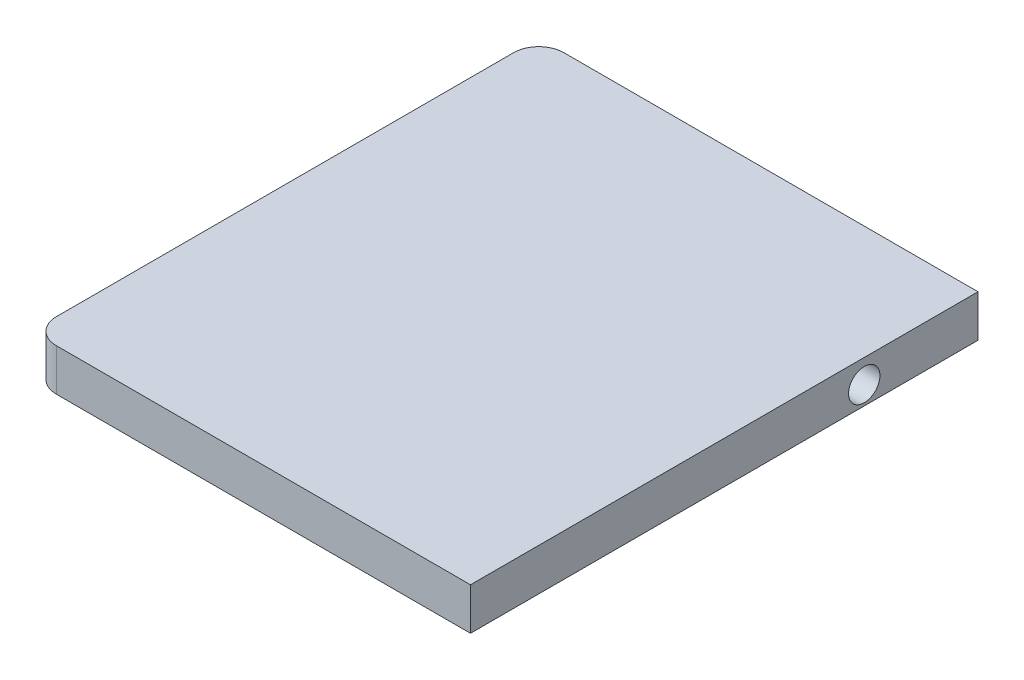
SolidWorks part; units mm, degrees
material "PLA"
ref_plane "Front Plane" through (0, 0, 0) normal (0, 0, 1) x (1, 0, 0)
ref_plane "Top Plane" through (0, 0, 0) normal (0, 1, 0) x (1, 0, 0)
ref_plane "Right Plane" through (0, 0, 0) normal (1, 0, 0) x (0, 0, -1)
sketch "Sketch1" plane through (0, 0, 0) normal (0, 1, 0) x (1, 0, 0)
  line L1 (22.225, -25.6794) -> (-22.225, -25.6794)
  line L2 (22.225, -25.6794) -> (22.225, 25.6794)
  line L3 (22.225, 25.6794) -> (-22.225, 25.6794)
  line L4 (-22.225, -25.6794) -> (-22.225, 25.6794)
  line L5 (22.225, -25.6794) -> (-22.225, 25.6794) construction
  line L6 (22.225, 25.6794) -> (-22.225, -25.6794) construction
  point P0 (0, 0)
  dimension "D1" = 51.3588
  dimension "D2" = 44.45
extrude "Boss-Extrude1" add sketch "Sketch1" along normal blind 4.7625
sketch "Sketch2" plane through (22.225, 0, 0) normal (1, 0, 0) x (0, 0, -1)
  line L0 (14.17, 4.7625) -> (14.17, 0)
  line L1 (-25.6794, 4.7625) -> (25.6794, 4.7625) construction
  line L2 (-25.6794, 0) -> (25.6794, 0) construction
  line L3 (25.6794, 4.7625) -> (25.6794, 0) construction
  circle A0 centre (14.17, 2.3813) radius 1.5875
  point P11 (14.17, 2.3813)
  dimension "D2" = 3.175
  dimension "D1" = 11.5094
extrude "Cut-Extrude1" cut sketch "Sketch2" against normal blind 29.9402 contours L0 A0 | L0 A0
fillet "Fillet1" radius 2.54 2 edges at (-22.225, 2.3813, -25.6794) (-22.225, 2.3813, 25.6794)
chamfer "Chamfer1" distance 0.508 angle 45 6 edges at (-21.4811, 0, 24.9355) (1.27, 0, 25.6794) (22.225, 0, 0) (1.27, 0, -25.6794) (-21.4811, 0, -24.9355) (-22.225, 0, 0)
